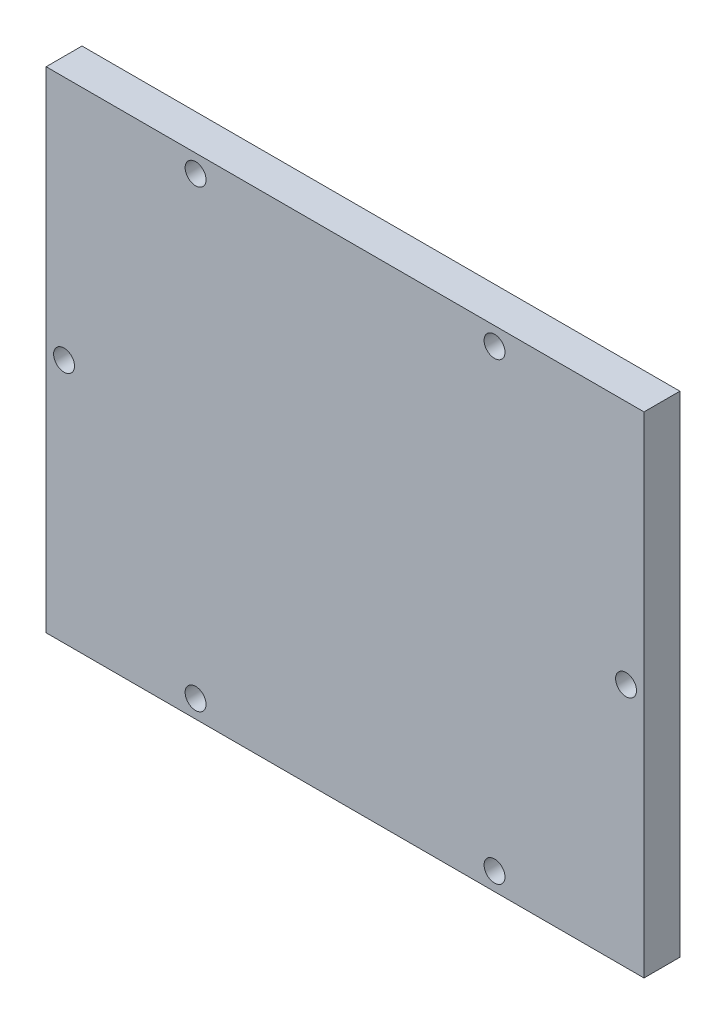
SolidWorks part; units mm, degrees
ref_plane "Plan de face" through (0, 0, 0) normal (0, 0, 1) x (1, 0, 0)
ref_plane "Plan de dessus" through (0, 0, 0) normal (0, 1, 0) x (1, 0, 0)
ref_plane "Plan de droite" through (0, 0, 0) normal (1, 0, 0) x (0, 0, -1)
sketch "Esquisse1" plane through (0, 0, 0) normal (0, 0, 1) x (1, 0, 0)
  line L1 (-50, -41) -> (50, -41)
  line L2 (-50, -41) -> (-50, 41)
  line L3 (-50, 41) -> (50, 41)
  line L4 (50, -41) -> (50, 41)
  line L5 (-50, -41) -> (50, 41) construction
  line L6 (-50, 41) -> (50, -41) construction
  point P0 (0, 0)
  dimension "D1" = 82
  dimension "D2" = 100
extrude "Boss.-Extru.1" add sketch "Esquisse1" along normal blind 6
sketch "Esquisse2" plane through (0, 0, 0) normal (0, 0, 1) x (1, 0, 0)
  line L0 (-81.9731, -38) -> (83.9393, -38) construction
  line L1 (-50, -41) -> (50, -41) construction
  line L2 (0, 0) -> (0, -49.9002) construction
  line L3 (-50, 41) -> (-50, -41) construction
  line L5 (-25, 38) -> (82.6895, 38) construction
  line L6 (50, 41) -> (-50, 41) construction
  circle A0 centre (-25, -38) radius 1.75
  circle A1 centre (25, -38) radius 1.75
  circle A2 centre (-25, 38) radius 1.75
  circle A3 centre (25, 38) radius 1.75
  dimension "D2" = 3.5
  dimension "D4" = 3
  dimension "D5" = 25
  dimension "D1" = 3
  dimension "D3" = 25
extrude "Enlèv. mat.-Extru.1" cut sketch "Esquisse2" along normal up to surface (6 mm away) up to face at (0, 0, 6)
sketch "Esquisse3" plane through (0, 0, 0) normal (0, 0, 1) x (1, 0, 0)
  line L0 (-84.0905, 0) -> (94.0725, 0) construction
  line L1 (47, 56.9426) -> (47, -50.5904) construction
  line L2 (50, -41) -> (50, 41) construction
  circle A0 centre (47, 0) radius 1.75
  dimension "D2" = 3.5
  dimension "D1" = 3
extrude "Enlèv. mat.-Extru.2" cut sketch "Esquisse3" along normal up to surface (6 mm away) up to face at (23.25, -38, 6)
mirror "Symétrie1" about plane through (0, 0, 0) normal (1, 0, 0) of "Enlèv. mat.-Extru.2"
sketch "Sketch1" [suppressed] plane through (0, 0, 6) normal (0, 0, 1) x (1, 0, 0)
  line L0 (-34, -26) -> (-34, 24)
  line L1 (-34, -26) -> (1.5, -26)
  line L2 (-34, 24) -> (1.5, 24)
  line L3 (1.5, -26) -> (1.5, 24)
  line L5 (50, 41) -> (-50, 41) construction
  line L6 (-50, -41) -> (50, -41) construction
  line L7 (-50, 41) -> (-50, -41) construction
  dimension "D1" = 50
  dimension "D2" = 35.5
  dimension "D3" = 15
  dimension "D4" = 16
sketch "Sketch2" [suppressed] plane through (0, 0, 6) normal (0, 0, 1) x (1, 0, 0)
  line L0 (21.5, -5) -> (21.5, 3) construction
  line L1 (11.5, -5) -> (11.5, 3)
  line L2 (31.5, -5) -> (31.5, 3)
  line L5 (1.5, -26) -> (1.5, 24) construction
  line L7 (-34, 24) -> (1.5, 24) construction
  line L8 (36.5, 13) -> (36.5, -15) construction
  arc A0 (11.5, -5) -> (31.5, -5) centre (21.5, -5) ccw
  arc A1 (31.5, 3) -> (11.5, 3) centre (21.5, 3) ccw
  circle A2 centre (36.5, -15) radius 2
  circle A3 centre (36.5, 13) radius 2
  point P2 (21.5, -1)
  point P7 (11.5, -1)
  point P8 (31.5, -1)
  point P17 (36.5, -1)
  dimension "D2" = 8
  dimension "D4" = 21
  dimension "D5" = 28
  dimension "D6" = 4
  dimension "D7" = 4
  dimension "D1" = 20
  dimension "D3" = 20
  dimension "D8" = 15
  dimension "D9" = 0
extrude "Cut-Extrude1" [suppressed] cut sketch "Sketch1" against normal through all
extrude "Cut-Extrude2" [suppressed] cut sketch "Sketch2" against normal through all
fillet "Congé2" [suppressed] radius 1
fillet "Congé1" [suppressed] radius 1
sketch "Sketch3" [suppressed] plane through (0, 0, 0) normal (0, 0, -1) x (-1, 0, 0)
  line L0 (8.5, 24.5) -> (8.5, -22.5) construction
  line L1 (12.5, 24.5) -> (12.5, -22.5)
  line L2 (4.5, 24.5) -> (4.5, -22.5)
  line L3 (-49, 41) -> (49, 41) construction
  line L4 (-10.5, 3) -> (-10.5, -5) construction
  arc A0 (12.5, 24.5) -> (4.5, 24.5) centre (8.5, 24.5) ccw
  arc A1 (4.5, -22.5) -> (12.5, -22.5) centre (8.5, -22.5) ccw
  point P2 (8.5, 1)
  point P7 (8.5, 28.5)
  point P8 (8.5, -26.5)
  point P13 (4.5, 1)
  dimension "D1" = 8
  dimension "D2" = 55
  dimension "D3" = 12.5
  dimension "D4" = 15
extrude "Cut-Extrude3" [suppressed] cut sketch "Sketch3" against normal through all
